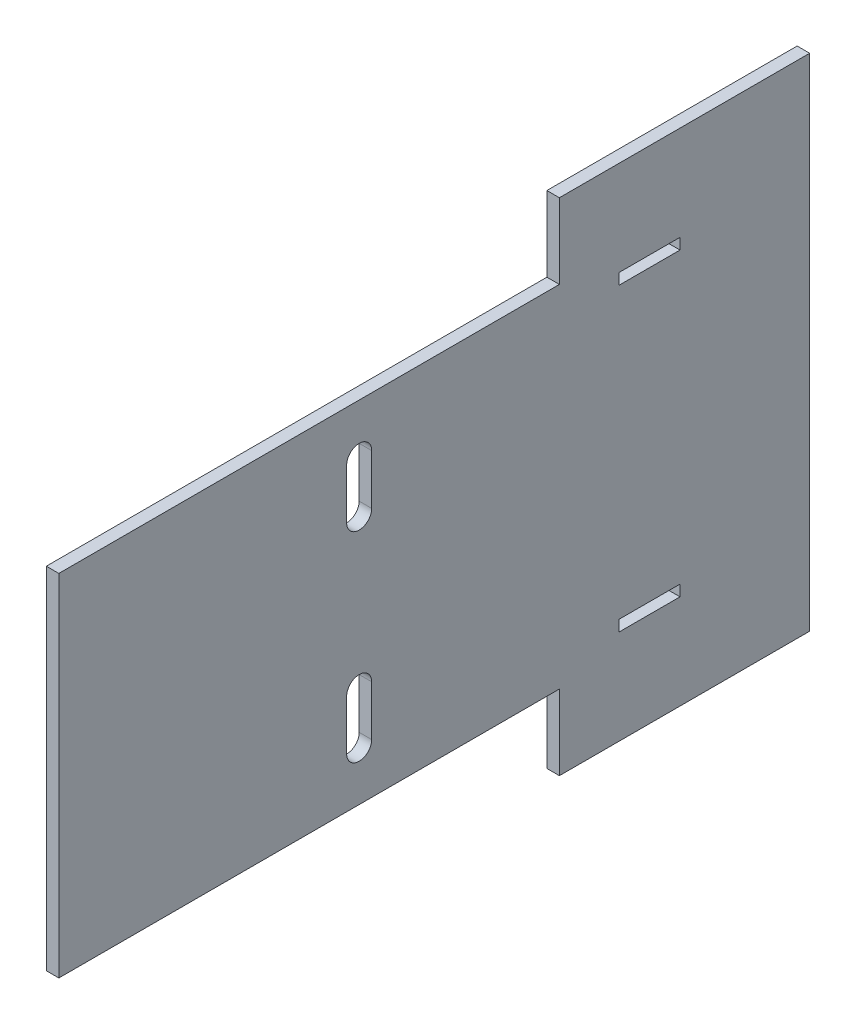
SolidWorks part; units mm, degrees
ref_plane "Front Plane" through (0, 0, 0) normal (1, 0, 0) x (0, 1, 0)
ref_plane "Top Plane" through (0, 0, 0) normal (0, 0, 1) x (0, 1, 0)
ref_plane "Right Plane" through (0, 0, 0) normal (0, 1, 0) x (-1, 0, 0)
sketch "Sketch1" plane through (0, 0, 0) normal (1, 0, 0) x (0, 1, 0)
  line L1 (50, 0) -> (50, 50)
  line L2 (50, 50) -> (35, 50)
  line L3 (35, 50) -> (35, 150)
  line L4 (35, 150) -> (-35, 150)
  line L5 (-35, 150) -> (-35, 50)
  line L6 (-35, 50) -> (-50, 50)
  line L7 (-50, 50) -> (-50, 0)
  line L8 (-50, 0) -> (0, 0)
  line L9 (0, 0) -> (50, 0)
  dimension "D1" = 50
  dimension "D2" = 50
  dimension "D3" = 70
  dimension "D4" = 100
extrude "Boss-Extrude1" add sketch "Sketch1" along normal blind 2.5 contours L5 L6 L7 L8 L9 L1 L2 L3 L4
sketch "Sketch4" plane through (0, 0, 0) normal (-1, 0, 0) x (0, -1, 0)
  line L0 (-28.9, 38.1) -> (-28.9, 25.9)
  line L1 (-28.9, 25.9) -> (-31.1, 25.9)
  line L2 (-31.1, 25.9) -> (-31.1, 38.1)
  line L3 (-31.1, 38.1) -> (-28.9, 38.1)
  line L4 (0, 0) -> (0, 150) construction
  line L5 (-35, 150) -> (35, 150) construction
  line L6 (-28.9, 32) -> (0, 32) construction
  line L7 (28.9, 38.1) -> (31.1, 38.1)
  line L8 (28.9, 38.1) -> (28.9, 25.9)
  line L9 (28.9, 25.9) -> (31.1, 25.9)
  line L10 (31.1, 38.1) -> (31.1, 25.9)
  line L11 (0, 32) -> (28.9, 32) construction
extrude "Cut-Extrude1" cut sketch "Sketch4" against normal through all
sketch "Sketch6" plane through (0, 0, 0) normal (-1, 0, 0) x (0, -1, 0)
  line L0 (-25, 92.5) -> (-15, 92.5)
  line L1 (15, 92.5) -> (25, 92.5)
  line L2 (25, 87.5) -> (15, 87.5)
  line L3 (-15, 87.5) -> (-25, 87.5)
  line L4 (-25, 90) -> (-35, 90) construction
  line L5 (-35, 50) -> (-35, 150) construction
  line L6 (25, 90) -> (35, 90) construction
  line L7 (35, 150) -> (35, 50) construction
  line L8 (-35, 150) -> (35, 150) construction
  arc A0 (-25, 87.5) -> (-25, 92.5) centre (-25, 90) cw
  arc A1 (-15, 92.5) -> (-15, 87.5) centre (-15, 90) cw
  arc A2 (15, 92.5) -> (15, 87.5) centre (15, 90) ccw
  arc A3 (25, 92.5) -> (25, 87.5) centre (25, 90) cw
  dimension "D1" = 5
  dimension "D2" = 10
  dimension "D3" = 30
  dimension "D4" = 60
extrude "Cut-Extrude2" cut sketch "Sketch6" against normal through all
